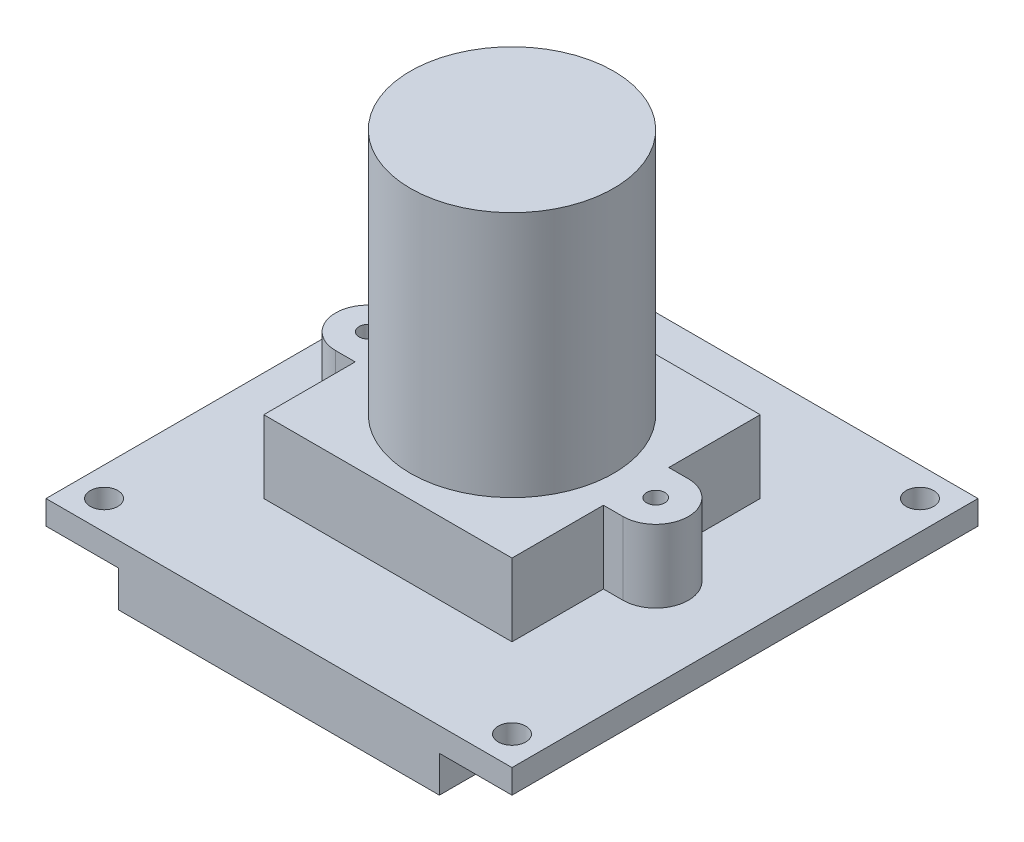
SolidWorks part; units mm, degrees
ref_plane "Front Plane" through (0, 0, 0) normal (0, 0, 1) x (1, 0, 0)
ref_plane "Top Plane" through (0, 0, 0) normal (0, 1, 0) x (1, 0, 0)
ref_plane "Right Plane" through (0, 0, 0) normal (1, 0, 0) x (0, 0, -1)
sketch "Sketch1" plane through (0, 0, 0) normal (0, 1, 0) x (1, 0, 0)
  line L0 (0, 0) -> (0, 16.05) construction
  line L1 (-16.05, 16.05) -> (16.05, 16.05)
  line L2 (-16.05, 16.05) -> (-16.05, -16.05)
  line L3 (-16.05, -16.05) -> (16.05, -16.05)
  line L4 (16.05, 16.05) -> (16.05, -16.05)
  line L5 (0, 0) -> (-16.05, 0) construction
  line L6 (-14.05, 13.1) -> (-14.05, -13.1) construction
  line L7 (-13.1, 14.05) -> (13.1, 14.05) construction
  circle A0 centre (-14.05, 14.05) radius 0.95
  circle A1 centre (14.05, 14.05) radius 0.95
  circle A2 centre (14.05, -14.05) radius 0.95
  circle A3 centre (-14.05, -14.05) radius 0.95
  point P4 (0, 16.05)
  point P6 (-16.05, 0)
  point P20 (-8.025, 0)
  point P23 (0, 8.025)
  dimension "D2" = 1.9
  dimension "D1" = 32.1
  dimension "D3" = 26.2
extrude "Boss-Extrude1" add sketch "Sketch1" along normal blind 1.65
sketch "Sketch2" plane through (0, 0, 0) normal (0, -1, 0) x (1, 0, 0)
  line L0 (-16.05, 16.05) -> (16.05, 16.05) construction
  line L1 (-11.05, 16.05) -> (11.05, 16.05)
  line L2 (-11.05, 16.05) -> (-11.05, 9.3)
  line L3 (-11.05, 9.3) -> (11.05, 9.3)
  line L4 (11.05, 16.05) -> (11.05, 9.3)
  point P6 (0, 9.3)
  dimension "D1" = 6.75
  dimension "D2" = 5
extrude "Boss-Extrude2" add sketch "Sketch2" along normal blind 2.5
sketch "Sketch3" plane through (0, 1.65, 0) normal (0, 1, 0) x (1, 0, 0)
  line L0 (9.9, 2.25) -> (8.55, 2.25)
  line L1 (-8.55, 8.55) -> (8.55, 8.55)
  line L3 (-8.55, -8.55) -> (8.55, -8.55)
  line L5 (9.9, -2.25) -> (8.55, -2.25)
  line L6 (8.55, 8.55) -> (8.55, 2.25)
  line L7 (8.55, -2.25) -> (8.55, -8.55)
  line L8 (0, 8.55) -> (0, 0) construction
  line L9 (-8.55, -2.25) -> (-8.55, -8.55)
  line L10 (-8.55, 8.55) -> (-8.55, 2.25)
  line L11 (-9.9, -2.25) -> (-8.55, -2.25)
  line L12 (-9.9, 2.25) -> (-8.55, 2.25)
  line L13 (-8.55, 8.55) -> (-8.55, -8.55) construction
  arc A0 (9.9, 2.25) -> (9.9, -2.25) centre (9.9, 0) cw
  circle A1 centre (9.9, 0) radius 0.625
  circle A2 centre (-9.9, 0) radius 0.625
  arc A3 (-9.9, 2.25) -> (-9.9, -2.25) centre (-9.9, 0) ccw
  point P4 (0, 8.55)
  point P15 (12.15, 0)
  point P21 (-8.55, 0)
  dimension "D2" = 1.25
  dimension "D1" = 17.1
  dimension "D3" = 4.5
  dimension "D4" = 3.6
extrude "Boss-Extrude3" add sketch "Sketch3" along normal blind 5
sketch "Sketch4" plane through (0, 6.65, 0) normal (0, 1, 0) x (1, 0, 0)
  circle A0 centre (0, 0) radius 7
  dimension "D1" = 14
extrude "Boss-Extrude4" add sketch "Sketch4" along normal blind 17
